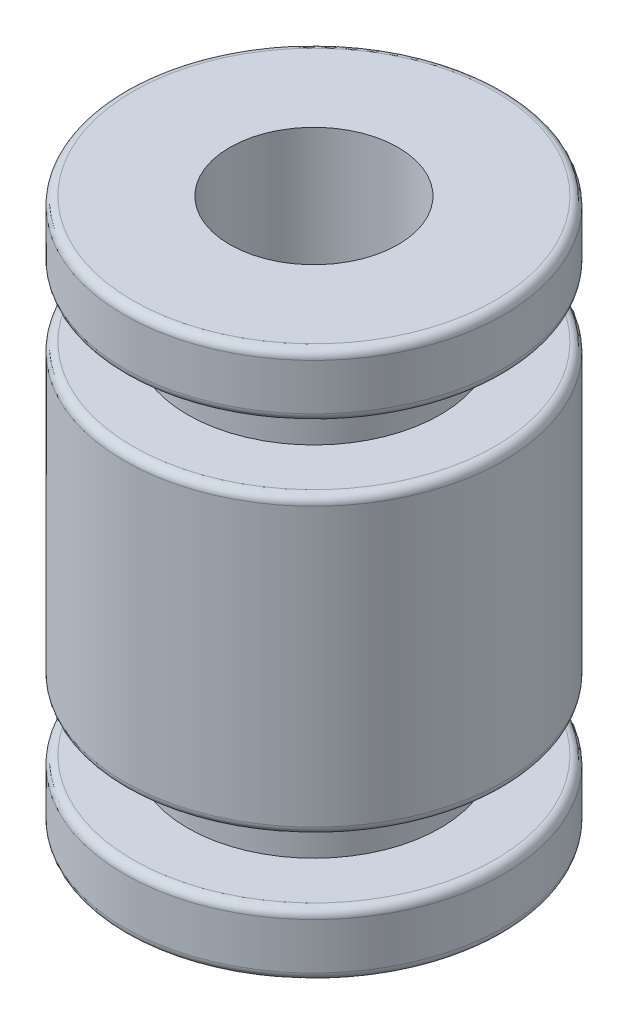
SolidWorks part; units mm, degrees
ref_plane "Front Plane" through (0, 0, 0) normal (0, 0, 1) x (1, 0, 0)
ref_plane "Top Plane" through (0, 0, 0) normal (0, 1, 0) x (1, 0, 0)
ref_plane "Right Plane" through (0, 0, 0) normal (1, 0, 0) x (0, 0, -1)
sketch "Sketch1" plane through (0, 0, 0) normal (0, 1, 0) x (1, 0, 0)
  circle A0 centre (0, 0) radius 2
  circle A1 centre (0, 0) radius 4.5
  dimension "D1" = 4
  dimension "D2" = 9
extrude "Boss-Extrude1" add sketch "Sketch1" along normal blind 1.5
sketch "Sketch2" plane through (0, 1.5, 0) normal (0, 1, 0) x (1, 0, 0)
  circle A0 centre (0, 0) radius 2
  circle A1 centre (0, 0) radius 3
  circle A2 centre (0, 0) radius 2 construction
  dimension "D1" = 6
extrude "Boss-Extrude2" add sketch "Sketch2" along normal blind 1.5
sketch "Sketch3" plane through (0, 3, 0) normal (0, 1, 0) x (1, 0, 0)
  circle A1 centre (0, 0) radius 2
  circle A2 centre (0, 0) radius 4.5
  circle A3 centre (0, 0) radius 2 construction
  circle A4 centre (0, 0) radius 4.5 construction
extrude "Boss-Extrude3" add sketch "Sketch3" along normal blind 7
sketch "Sketch4" plane through (0, 10, 0) normal (0, 1, 0) x (1, 0, 0)
  circle A0 centre (0, 0) radius 3 construction
  circle A1 centre (0, 0) radius 3
  circle A2 centre (0, 0) radius 4.5 construction
  circle A3 centre (0, 0) radius 4.5
  circle M2 centre (0, 0) radius 2
extrude "Boss-Extrude4" add sketch "Sketch4" along normal blind 1.5 contours A1 M2
sketch "Sketch5" plane through (0, 11.5, 0) normal (0, 1, 0) x (1, 0, 0)
  circle A0 centre (0, 0) radius 2 construction
  circle A1 centre (0, 0) radius 2
  circle A2 centre (0, 0) radius 4.5 construction
  circle A3 centre (0, 0) radius 4.5
extrude "Boss-Extrude5" add sketch "Sketch5" along normal blind 1.5
fillet "Fillet1" radius 0.2 6 edges at (0, 0, 4.5) (0, 1.5, 4.5) (0, 3, 4.5) (0, 10, 4.5) (0, 11.5, 4.5) (0, 13, 4.5)
